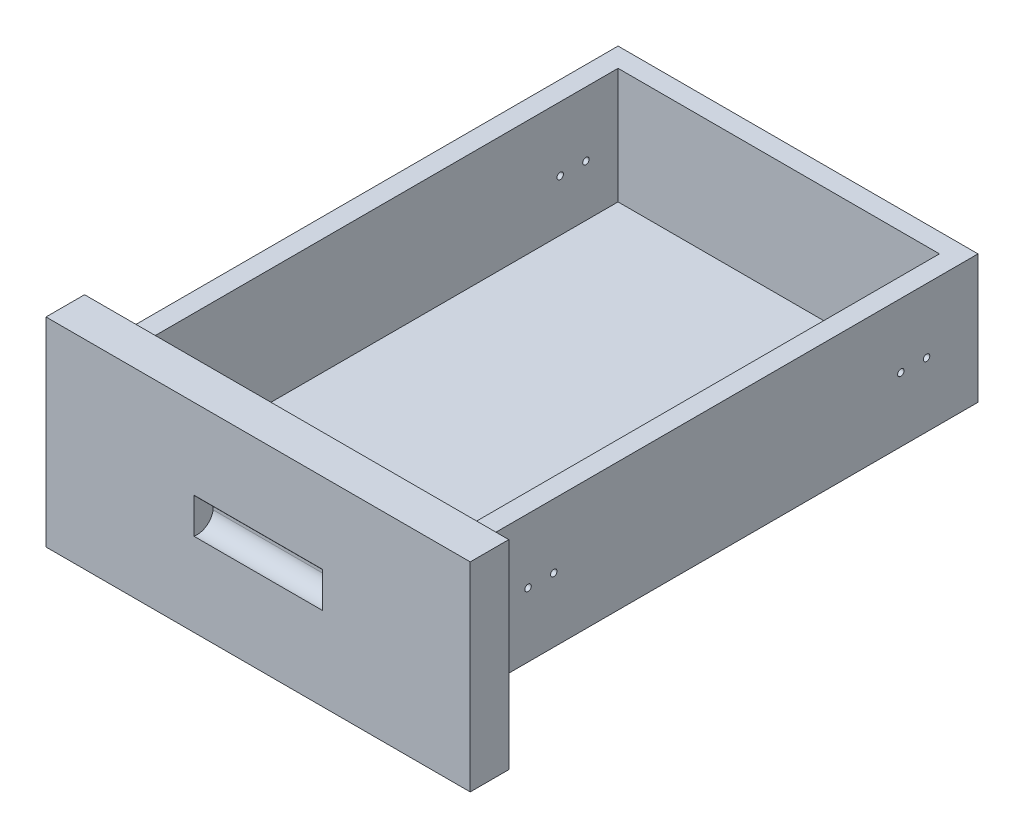
SolidWorks part; units mm, degrees
material "Teak"
ref_plane "Front Plane" through (0, 0, 0) normal (0, 0, 1) x (1, 0, 0)
ref_plane "Top Plane" through (0, 0, 0) normal (0, 1, 0) x (1, 0, 0)
ref_plane "Right Plane" through (0, 0, 0) normal (1, 0, 0) x (0, 0, -1)
sketch "Sketch1" plane through (0, 0, 0) normal (0, 0, 1) x (1, 0, 0)
  line L1 (165, -77.5) -> (-165, -77.5)
  line L2 (165, -77.5) -> (165, 77.5)
  line L3 (165, 77.5) -> (-165, 77.5)
  line L4 (-165, -77.5) -> (-165, 77.5)
  line L5 (165, -77.5) -> (-165, 77.5) construction
  line L6 (165, 77.5) -> (-165, -77.5) construction
  point P0 (0, 0)
  dimension "D1" = 330
  dimension "D2" = 155
extrude "Boss-Extrude1" add sketch "Sketch1" along normal blind 30
sketch "Sketch2" plane through (0, 0, 0) normal (0, 0, -1) x (-1, 0, 0)
  line L0 (-165, -77.5) -> (-165, 77.5) construction
  line L1 (140, -37.5) -> (-140, -37.5)
  line L2 (140, -37.5) -> (140, 62.5)
  line L3 (140, 62.5) -> (-140, 62.5)
  line L4 (-140, -37.5) -> (-140, 62.5)
  line L5 (140, -37.5) -> (-140, 62.5) construction
  line L6 (140, 62.5) -> (-140, -37.5) construction
  line L7 (165, -77.5) -> (-165, -77.5) construction
  line L8 (-165, 77.5) -> (165, 77.5) construction
  point P0 (0, 12.5)
  dimension "D1" = 25
  dimension "D2" = 40
  dimension "D3" = 15
extrude "Boss-Extrude2" add sketch "Sketch2" along normal blind 390
sketch "Sketch3" plane through (0, 62.5, 0) normal (0, 1, 0) x (1, 0, 0)
  line L0 (165, 0) -> (-165, 0) construction
  line L1 (-125, 0) -> (125, 0)
  line L2 (-125, 0) -> (-125, 375)
  line L3 (-125, 375) -> (125, 375)
  line L4 (125, 0) -> (125, 375)
  line L5 (-140, 390) -> (-140, 0) construction
  line L6 (140, 390) -> (140, 0) construction
  line L7 (-140, 390) -> (140, 390) construction
  dimension "D1" = 15
  dimension "D2" = 15
  dimension "D3" = 15
extrude "Cut-Extrude1" cut sketch "Sketch3" against normal blind 90
sketch "Sketch4" plane through (0, 0, 0) normal (1, 0, 0) x (0, 0, -1)
  line L0 (-35.7149, 8.7911) -> (-23.3513, 19.9574)
  line L1 (-15, 16.2468) -> (-15, -2.5)
  line L2 (-30, 77.5) -> (0, 77.5) construction
  line L3 (-30, -77.5) -> (-30, 77.5) construction
  arc A0 (-15, -2.5) -> (-35.7149, 8.7911) centre (-27.3366, -0.4855) cw
  arc A1 (-23.3513, 19.9574) -> (-15, 16.2468) centre (-20, 16.2468) cw
  point P10 (-15, 27.5)
  dimension "D4" = 5
  dimension "D5" = 12.5
  dimension "D1" = 50
  dimension "D2" = 30
  dimension "D3" = 15
  dimension "D6" = 18.7468
extrude "Cut-Extrude2" cut sketch "Sketch4" against normal mid plane 100 contours L0 A1 L1 A0
fillet "Fillet1" radius 0.5 1 edges at (0, 13.9525, 30)
sketch "Sketch7" plane through (140, 0, 0) normal (1, 0, 0) x (0, 0, -1)
  line L0 (390, 12.5) -> (0, 12.5) construction
  line L1 (390, 62.5) -> (390, -37.5) construction
  line L2 (0, 62.5) -> (0, -37.5) construction
  line L3 (195, 12.5) -> (195, 62.5) construction
  line L4 (390, 62.5) -> (0, 62.5) construction
  circle A0 centre (350, 12.5) radius 2.5
  circle A1 centre (330, 12.5) radius 2.5
  circle A2 centre (60, 12.5) radius 2.5
  circle A3 centre (40, 12.5) radius 2.5
  dimension "D3" = 5
  dimension "D1" = 40
  dimension "D2" = 20
extrude "Cut-Extrude3" cut sketch "Sketch7" against normal through all
